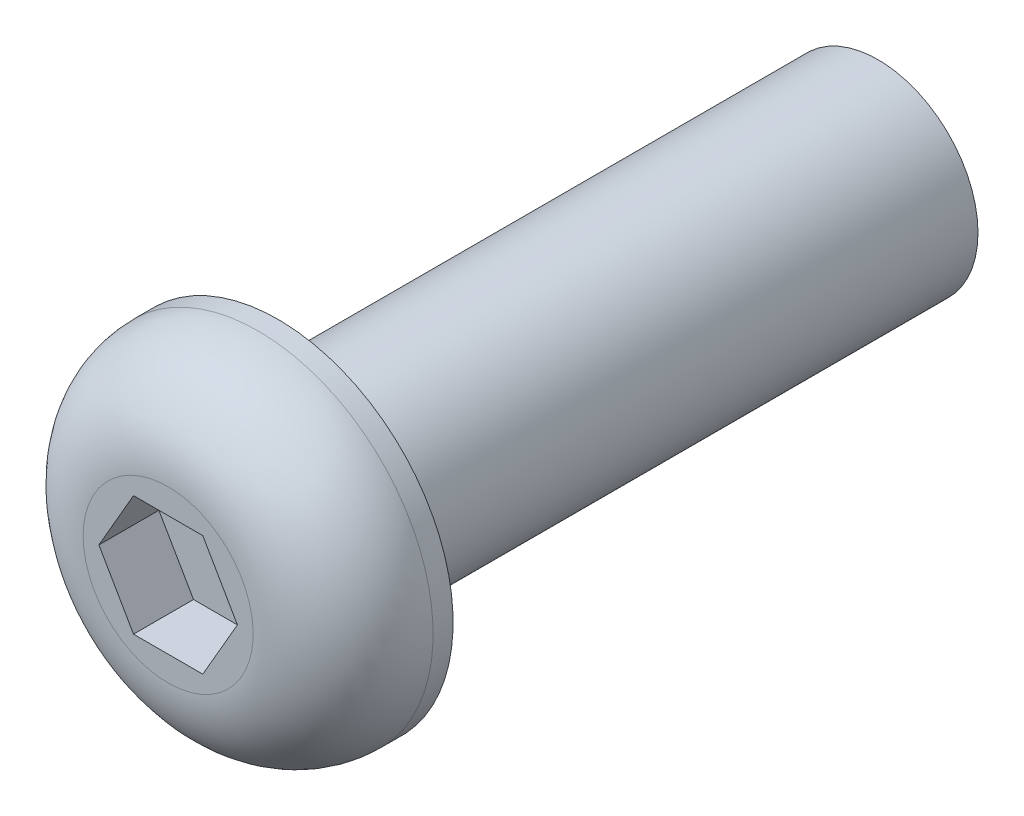
SolidWorks part; units mm, degrees
material "AISI 304"
ref_plane "Front Plane" through (0, 0, 0) normal (0, 0, 1) x (1, 0, 0)
ref_plane "Top Plane" through (0, 0, 0) normal (0, 1, 0) x (1, 0, 0)
ref_plane "Right Plane" through (0, 0, 0) normal (1, 0, 0) x (0, 0, -1)
sketch "Sketch1" plane through (0, 0, 0) normal (0, 0, 1) x (1, 0, 0)
  circle A0 centre (0, 0) radius 5
  dimension "D1" = 10
extrude "Extrude1" add sketch "Sketch1" against normal blind 30
sketch "Sketch2" plane through (0, 0, 0) normal (1, 0, 0) x (0, 0, -1)
  line L0 (0, 0) -> (-10.9859, 0) construction
  line L1 (0, 0) -> (0, 8.75)
  line L2 (0, 8.75) -> (-1, 8.75)
  line L3 (-5.5, 0) -> (-5.5, 4.25)
  line L4 (0, 0) -> (-5.5, 0)
  arc A0 (-5.5, 4.25) -> (-1, 8.75) centre (-1, 4.25) cw
  dimension "D1" = 5.5
  dimension "D2" = 17.5
  dimension "D3" = 1
revolve "Revolve1" add sketch "Sketch2" angle 360 about L0
sketch "Sketch3" plane through (0, 0, 5.5) normal (0, 0, 1) x (1, 0, 0)
  line L1 (-1.7321, 3) -> (-3.4641, 0)
  line L2 (-3.4641, 0) -> (-1.7321, -3)
  line L3 (-1.7321, -3) -> (1.7321, -3)
  line L4 (1.7321, -3) -> (3.4641, 0)
  line L5 (3.4641, 0) -> (1.7321, 3)
  line L6 (1.7321, 3) -> (-1.7321, 3)
  circle A0 centre (0, 0) radius 3 construction
  dimension "D1" = 6
extrude "Cut-Extrude1" cut sketch "Sketch3" against normal blind 3
